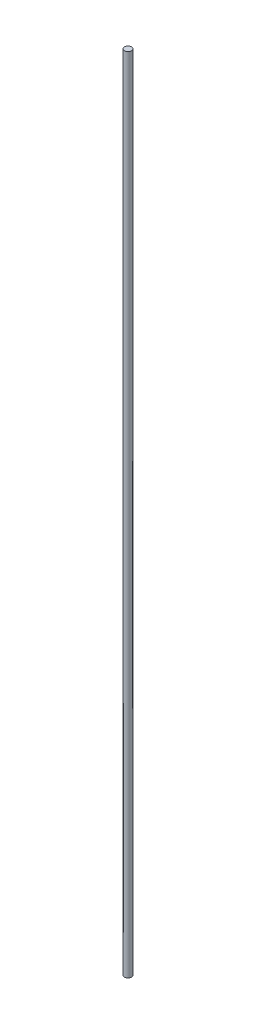
SolidWorks part; units mm, degrees
material "Nylon 101"
ref_plane "Alzado" through (0, 0, 0) normal (0, 0, 1) x (1, 0, 0)
ref_plane "Planta" through (0, 0, 0) normal (0, 1, 0) x (1, 0, 0)
ref_plane "Vista lateral" through (0, 0, 0) normal (1, 0, 0) x (0, 0, -1)
sketch "Sketch1" plane through (0, 0, 0) normal (0, 0, 1) x (1, 0, 0)
  line L0 (0, -1) -> (0.75, -1)
  line L1 (0.75, -1) -> (0.75, -175)
  line L2 (0.75, -175) -> (0, -175)
  line L3 (0, -175) -> (0, -1)
  line L4 (0, -179) -> (0, 3) construction
revolve "Varilla_carbono" add sketch "Sketch1" angle 360 about L4
